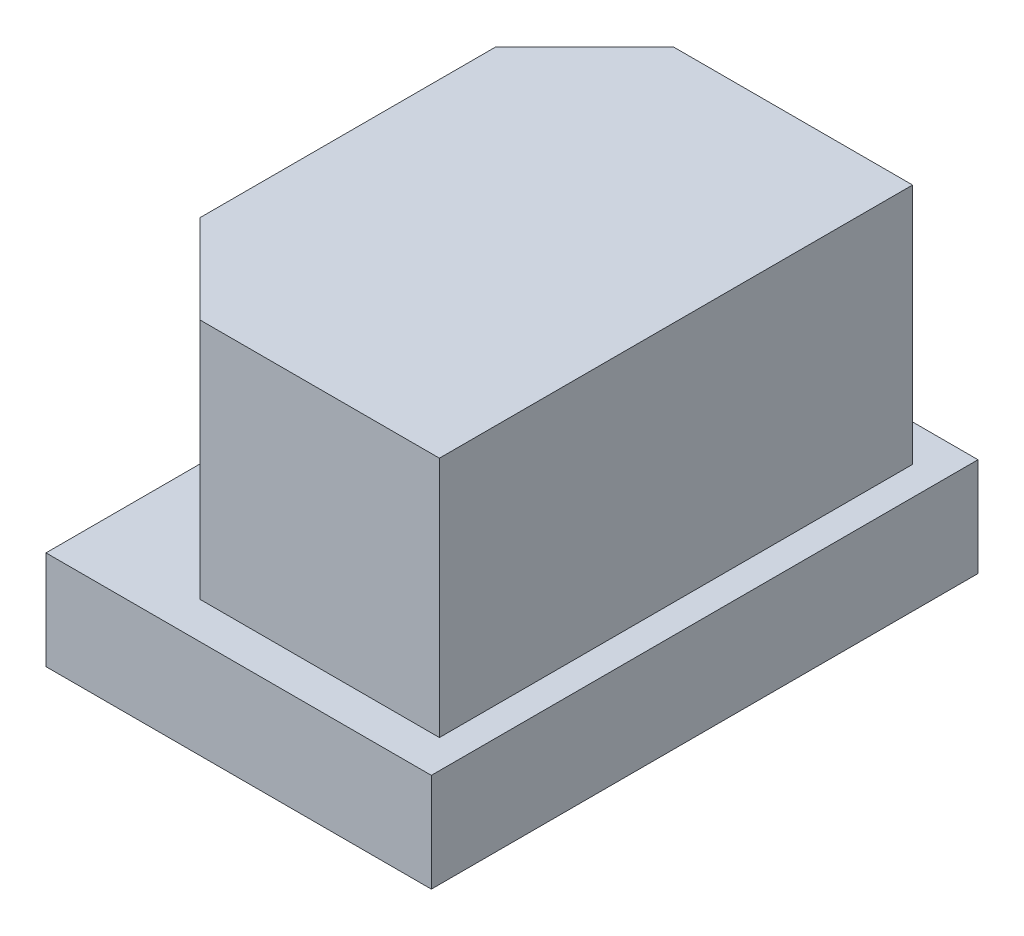
SolidWorks part; units mm, degrees
ref_plane "Front Plane" through (0, 0, 0) normal (0, 0, 1) x (1, 0, 0)
ref_plane "Top Plane" through (0, 0, 0) normal (0, 1, 0) x (1, 0, 0)
ref_plane "Right Plane" through (0, 0, 0) normal (1, 0, 0) x (0, 0, -1)
sketch "Sketch1" plane through (0, 0, 0) normal (0, 1, 0) x (1, 0, 0)
  line L0 (-13.3503, -26.4) -> (-18.3, -21.4503)
  line L1 (0, 0) -> (-13.3503, 0)
  line L2 (0, 0) -> (0, -26.4)
  line L3 (0, -26.4) -> (-13.3503, -26.4)
  line L4 (-18.3, -4.9497) -> (-18.3, -21.4503)
  line L5 (-13.3503, 0) -> (-18.3, -4.9497)
  point P1 (-18.3, -26.4)
  point P3 (-18.3, 0)
  dimension "D1" = 18.3
  dimension "D2" = 26.4
  dimension "D3" = 135
  dimension "D4" = 135
  dimension "D5" = 7
extrude "Boss-Extrude1" add sketch "Sketch1" along normal blind 13.5
sketch "Sketch2" plane through (0, 0, 0) normal (0, -1, 0) x (1, 0, 0)
  line L0 (-18.3, 13.2) -> (0, 13.2) construction
  line L1 (-18.3, 4.9497) -> (-18.3, 21.4503) construction
  line L2 (0, 26.4) -> (0, 0) construction
  line L5 (-19.9, -2.05) -> (1.6, -2.05)
  line L7 (-19.9, -2.05) -> (-19.9, 28.45)
  line L8 (-19.9, 28.45) -> (1.6, 28.45)
  line L9 (1.6, -2.05) -> (1.6, 28.45)
  line L10 (-19.9, -2.05) -> (1.6, 28.45) construction
  line L11 (-19.9, 28.45) -> (1.6, -2.05) construction
  point P6 (-9.15, 13.2)
  dimension "D1" = 21.5
  dimension "D2" = 30.5
extrude "Boss-Extrude2" add sketch "Sketch2" along normal blind 5.5
